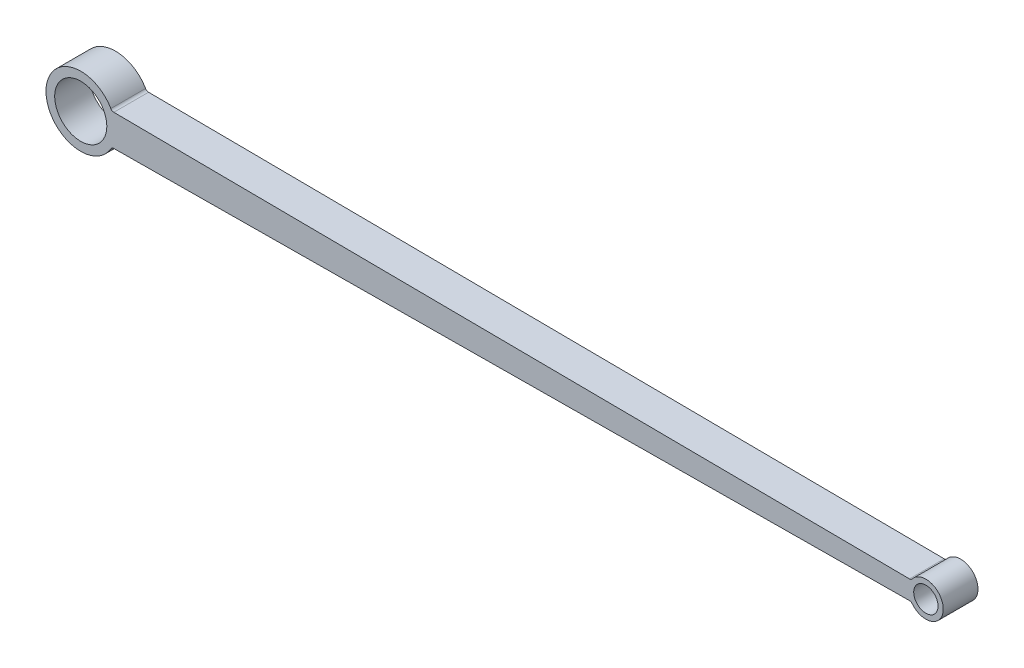
SolidWorks part; units mm, degrees
ref_plane "Plano frontal" through (0, 0, 0) normal (0, 0, 1) x (1, 0, 0)
ref_plane "Plano superior" through (0, 0, 0) normal (0, 1, 0) x (1, 0, 0)
ref_plane "Plano direito" through (0, 0, 0) normal (1, 0, 0) x (0, 0, -1)
sketch "Esboço1" plane through (0, 0, 0) normal (0, 0, 1) x (1, 0, 0)
  line L0 (-44.2844, 0) -> (263.3624, 0) construction
  line L1 (9.5142, -4.5073) -> (238.4731, -2.7055)
  line L2 (9.5142, 4.5073) -> (238.4731, 2.7055)
  circle A0 centre (0, 0) radius 7.5
  arc A1 (239.2675, -3.0879) -> (239.2675, 3.0879) centre (243.2, 0) ccw
  arc A2 (8.6564, 5.0066) -> (8.6564, -5.0066) centre (0, 0) ccw
  circle A3 centre (243.2, 0) radius 3.5
  arc A4 (238.4731, 2.7055) -> (239.2675, 3.0879) centre (238.481, 3.7055) ccw
  arc A5 (238.4731, -2.7055) -> (239.2675, -3.0879) centre (238.481, -3.7055) cw
  arc A6 (9.5142, 4.5073) -> (8.6564, 5.0066) centre (9.5221, 5.5073) cw
  arc A7 (9.5142, -4.5073) -> (8.6564, -5.0066) centre (9.5221, -5.5073) ccw
  point P11 (173.4904, 0)
  point P12 (263.3624, 0)
  point P15 (238.9926, 2.7014)
  point P18 (238.9926, -2.7014)
  point P21 (8.9243, 4.5119)
  point P24 (8.9243, -4.5119)
  dimension "D1" = 15
  dimension "D2" = 20
  dimension "D3" = 10
  dimension "D4" = 243.2
  dimension "D5" = 7
  dimension "D6" = 1
  dimension "D7" = 1
  dimension "D8" = 1
  dimension "D9" = 1
extrude "Ressalto-extrusão1" add sketch "Esboço1" along normal blind 10
